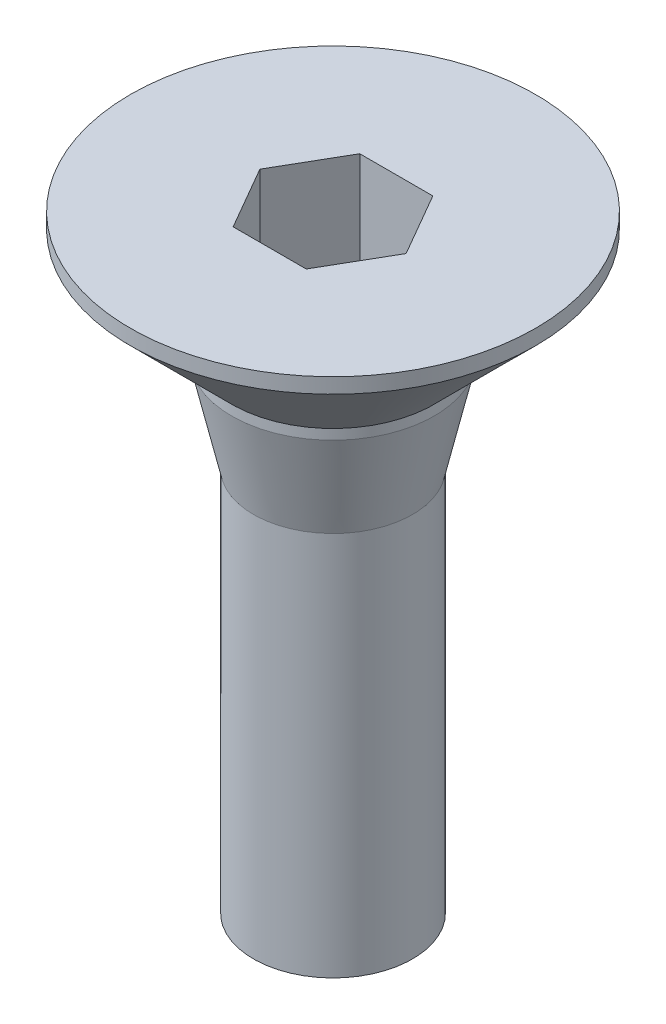
SolidWorks part; units mm, degrees
ref_plane "Vorne" through (0, 0, 0) normal (0, 0, 1) x (1, 0, 0)
ref_plane "Oben" through (0, 0, 0) normal (0, 1, 0) x (1, 0, 0)
ref_plane "Rechts" through (0, 0, 0) normal (1, 0, 0) x (0, 0, -1)
sketch "Skizze1" plane through (0, 0, 0) normal (0, 0, 1) x (1, 0, 0)
  line L0 (0, 0) -> (4, 0)
  line L1 (4, 0) -> (4, -0.3)
  line L2 (4, -0.3) -> (2, -2.3)
  line L3 (2, -2.3) -> (2, -2.5)
  line L4 (2, -2.5) -> (1.5705, -4.4)
  line L5 (1.5705, -4.4) -> (1.5705, -12)
  line L6 (1.5705, -12) -> (0, -12)
  line L7 (0, -12) -> (0, 0)
  line L8 (0, 0) -> (0, -12) construction
  dimension "DK" = 3.141
  dimension "D2" = 45
  dimension "DG" = 4
  dimension "DA" = 8
  dimension "K" = 2.3
  dimension "LS" = 2.5
  dimension "LG" = 4.4
  dimension "L" = 12
revolve "Basis-Rotation" add sketch "Skizze1" angle 360 about L8
sketch "Skizze2" plane through (0, 0, 0) normal (0, 1, 0) x (-1, 0, 0)
  line L0 (1.4434, 0) -> (-1.4434, 0) construction
  line L1 (0, 1.25) -> (0, -1.25) construction
  line L2 (0.7217, -1.25) -> (-0.7217, -1.25)
  line L3 (-0.7217, -1.25) -> (-1.4434, 0)
  line L4 (0.7217, -1.25) -> (1.4434, 0)
  line L5 (0.7217, 1.25) -> (1.4434, 0)
  line L6 (-0.7217, 1.25) -> (-1.4434, 0)
  line L7 (0.7217, 1.25) -> (-0.7217, 1.25)
  dimension "D2" = 120
extrude "Schnitt-Linear austragen1" cut sketch "Skizze2" against normal blind 5.3
